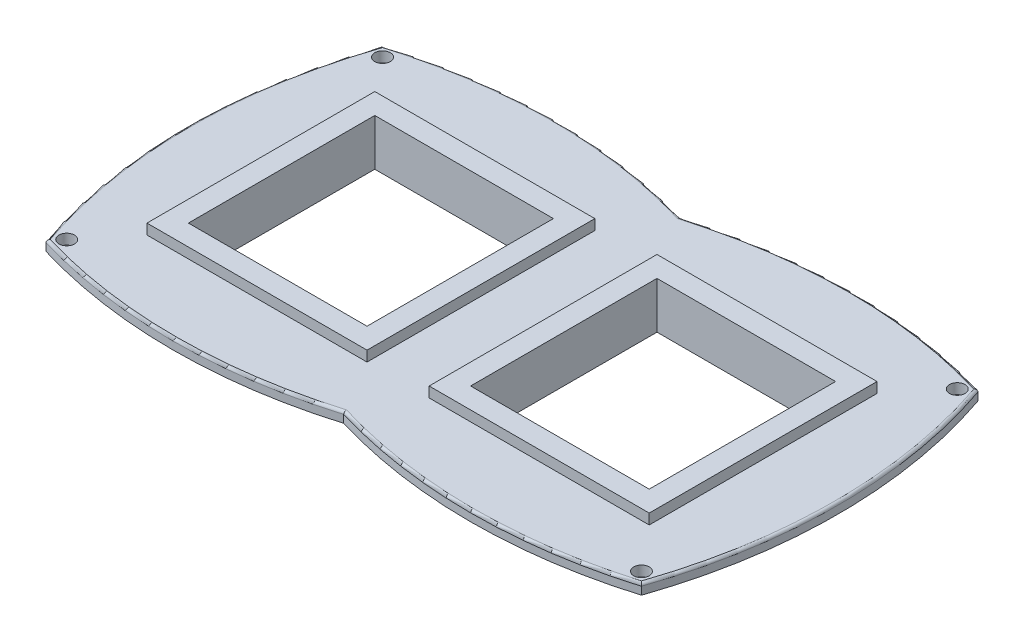
SolidWorks part; units mm, degrees
ref_plane "Front Plane" through (0, 0, 0) normal (0, 0, 1) x (1, 0, 0)
ref_plane "Top Plane" through (0, 0, 0) normal (0, 1, 0) x (1, 0, 0)
ref_plane "Right Plane" through (0, 0, 0) normal (1, 0, 0) x (0, 0, -1)
sketch "Sketch1" plane through (0, 0, 0) normal (0, 1, 0) x (1, 0, 0)
  line L1 (-57.5, 32.5) -> (57.5, 32.5)
  line L2 (-57.5, 32.5) -> (-57.5, -32.5)
  line L3 (-57.5, -32.5) -> (57.5, -32.5)
  line L4 (57.5, 32.5) -> (57.5, -32.5)
  line L5 (-57.5, 32.5) -> (57.5, -32.5) construction
  line L6 (-57.5, -32.5) -> (57.5, 32.5) construction
  point P0 (0, 0)
  dimension "D1" = 115
  dimension "D2" = 65
sketch "Sketch2" plane through (0, 0, 0) normal (0, 1, 0) x (1, 0, 0)
  line L0 (-57.5, 32.5) -> (57.5, 32.5) construction
  line L1 (-57.5, -32.5) -> (57.5, -32.5) construction
  arc A0 (-57.5, 32.5) -> (0, 32.5) centre (-28.75, -63.2781) cw
  arc A1 (0, 32.5) -> (57.5, 32.5) centre (28.75, -63.2781) cw
  arc A2 (57.5, 32.5) -> (57.5, -32.5) centre (-37.0714, 0) cw
  arc A3 (-57.5, -32.5) -> (0, -32.5) centre (-28.75, 63.2781) ccw
  arc A4 (0, -32.5) -> (57.5, -32.5) centre (28.75, 63.2781) ccw
  arc A5 (-57.5, -32.5) -> (-57.5, 32.5) centre (37.0714, 0) cw
  dimension "D1" = 100
  dimension "D2" = 100
  dimension "D3" = 100
  dimension "D4" = 100
  dimension "D5" = 100
  dimension "D6" = 100
extrude "Boss-Extrude1" add sketch "Sketch2" along normal blind 2
sketch "Sketch3" plane through (0, 2, 0) normal (0, 1, 0) x (1, 0, 0)
  point P0 (-55.5, 30.5)
  point P1 (55.5, 30.5)
  point P2 (55.5, -30.5)
  point P5 (-55.5, -30.5)
  dimension "D1" = 2
  dimension "D2" = 2
  dimension "D3" = 2
  dimension "D4" = 2
  dimension "D5" = 2
  dimension "D6" = 2
  dimension "D7" = 2
  dimension "D8" = 2
hole_wizard "Hole1" positions "Sketch4" profile "Sketch5" legacy
sketch "Sketch4" plane through (0, 2, 0) normal (0, 1, 0) x (1, 0, 0)
  point P0 (-55.5, 30.5)
  point P3 (55.5, 30.5)
  point P6 (55.5, -30.5)
  point P9 (-55.5, -30.5)
sketch "Sketch5" plane through (-55.5, 2, -30.5) normal (1, 0, 0) x (0, 0, 1)
  line L0 (0, 0) -> (0, 10)
  line L1 (0, 10) -> (1.5, 10)
  line L2 (1.5, 10) -> (1.5, 0)
  line L3 (1.5, 0) -> (0, 0)
  line L4 (0, 110) -> (0, -10) construction
  dimension "Diameter" = 3
  dimension "Depth" = 10
fillet "Fillet1" radius 0.5 6 edges at (62.9286, 2, 0) (28.75, 2, 36.7219) (-28.75, 2, 36.7219) (-28.75, 2, -36.7219) (28.75, 2, -36.7219) (-62.9286, 2, 0)
sketch "Sketch7" plane through (0, 2, 0) normal (0, 1, 0) x (1, 0, 0)
  line L1 (-44.5, 18) -> (-10, 18)
  line L2 (-44.5, 18) -> (-44.5, -18)
  line L3 (-44.5, -18) -> (-10, -18)
  line L4 (-10, 18) -> (-10, -18)
  line L5 (-44.5, 18) -> (-10, -18) construction
  line L6 (-44.5, -18) -> (-10, 18) construction
  point P0 (-27.25, 0)
  dimension "D1" = 34.5
  dimension "D2" = 36
  dimension "D3" = 10
extrude "Cut-Extrude1" cut sketch "Sketch7" against normal blind 2
sketch "Sketch9" plane through (0, 0, 0) normal (0, -1, 0) x (1, 0, 0)
  line L1 (-45.5, 19) -> (-9, 19)
  line L2 (-45.5, 19) -> (-45.5, -19)
  line L3 (-45.5, -19) -> (-9, -19)
  line L4 (-9, 19) -> (-9, -19)
  line L5 (-45.5, 19) -> (-9, -19) construction
  line L6 (-45.5, -19) -> (-9, 19) construction
  line L7 (-44.5, 18) -> (-10, 18)
  line L8 (-44.5, 18) -> (-44.5, -18)
  line L9 (-44.5, -18) -> (-10, -18)
  line L10 (-10, 18) -> (-10, -18)
  line L11 (-44.5, 18) -> (-10, -18) construction
  line L12 (-44.5, -18) -> (-10, 18) construction
  point P0 (-27.25, 0)
  point P6 (-27.25, 0)
  dimension "D1" = 34.5
  dimension "D2" = 36.5
  dimension "D3" = 36
  dimension "D4" = 38
extrude "Boss-Extrude2" add sketch "Sketch9" along normal blind 5
sketch "Sketch10" plane through (0, 2, 0) normal (0, 1, 0) x (1, 0, 0)
  line L0 (-10, 18) -> (-44.5, 18) construction
  line L1 (-48.5, 22) -> (-6, 22)
  line L2 (-48.5, 22) -> (-48.5, -22)
  line L3 (-48.5, -22) -> (-6, -22)
  line L4 (-6, 22) -> (-6, -22)
  line L5 (-48.5, 22) -> (-6, -22) construction
  line L6 (-48.5, -22) -> (-6, 22) construction
  line L8 (-44.5, 18) -> (-10, 18)
  line L9 (-44.5, 18) -> (-44.5, -18)
  line L10 (-44.5, -18) -> (-10, -18)
  line L11 (-10, 18) -> (-10, -18)
  line L12 (-44.5, 18) -> (-10, -18) construction
  line L13 (-44.5, -18) -> (-10, 18) construction
  point P0 (-27.25, 0)
  point P10 (-27.25, 18)
  point P11 (-27.25, 0)
  dimension "D1" = 42.5
  dimension "D2" = 44
extrude "Boss-Extrude3" add sketch "Sketch10" along normal blind 2
mirror "Mirror1" about plane through (0, 0, 0) normal (1, 0, 0) of "Boss-Extrude2", "Cut-Extrude1", "Boss-Extrude3"
